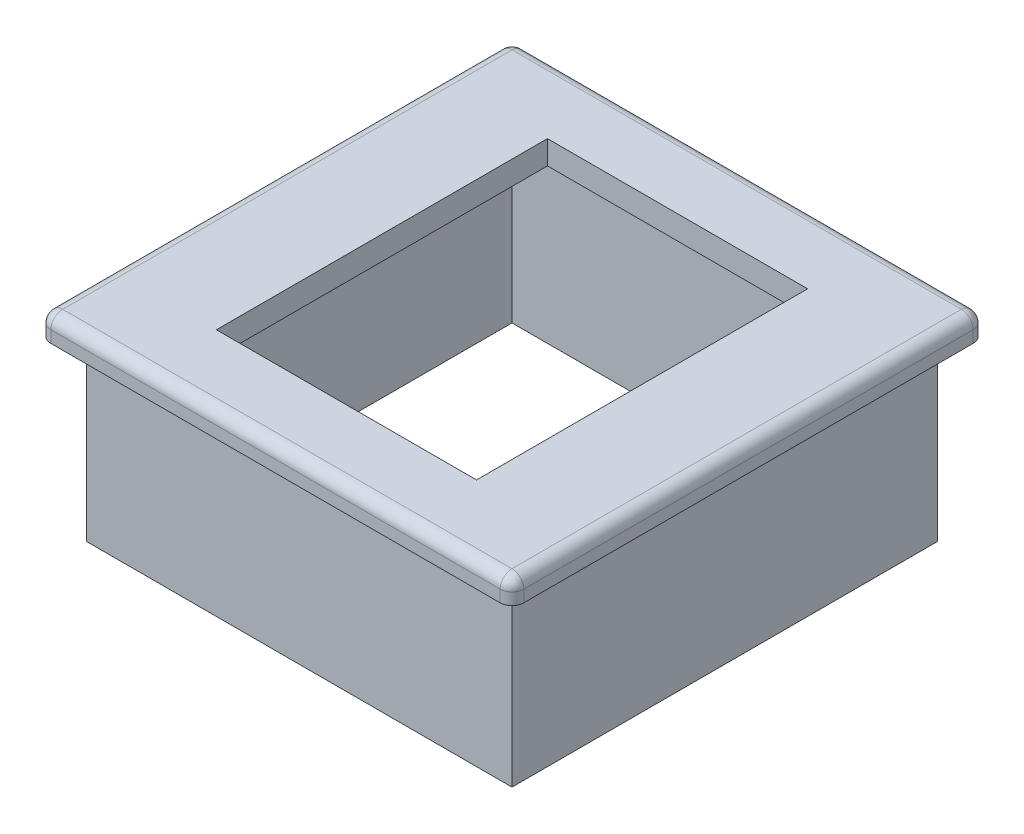
SolidWorks part; units mm, degrees
ref_plane "Front Plane" through (0, 0, 0) normal (0, 0, 1) x (1, 0, 0)
ref_plane "Top Plane" through (0, 0, 0) normal (0, 1, 0) x (1, 0, 0)
ref_plane "Right Plane" through (0, 0, 0) normal (1, 0, 0) x (0, 0, -1)
sketch "Sketch1" plane through (0, 0, 0) normal (0, 1, 0) x (1, 0, 0)
  line L1 (-20, 20) -> (20, 20)
  line L2 (-20, 20) -> (-20, -20)
  line L3 (-20, -20) -> (20, -20)
  line L4 (20, 20) -> (20, -20)
  line L5 (-20, 20) -> (20, -20) construction
  line L6 (-20, -20) -> (20, 20) construction
  line L7 (-11, 14) -> (11, 14)
  line L8 (-11, 14) -> (-11, -14)
  line L9 (-11, -14) -> (11, -14)
  line L10 (11, 14) -> (11, -14)
  line L11 (-11, 14) -> (11, -14) construction
  line L12 (-11, -14) -> (11, 14) construction
  point P0 (0, 0)
  point P6 (0, 0)
  dimension "D1" = 40
  dimension "D2" = 28
  dimension "D3" = 22
extrude "Boss-Extrude1" add sketch "Sketch1" along normal blind 2
sketch "Sketch2" plane through (0, 0, 0) normal (0, -1, 0) x (-1, 0, 0)
  line L1 (-20, 20) -> (20, 20)
  line L2 (-20, 20) -> (-20, -20)
  line L3 (-20, -20) -> (20, -20)
  line L4 (20, 20) -> (20, -20)
  line L5 (18, -18) -> (-18, -18)
  line L6 (18, -18) -> (18, 18)
  line L7 (18, 18) -> (-18, 18)
  line L8 (-18, -18) -> (-18, 18)
  line L9 (-16, 16) -> (16, 16)
  line L10 (-16, 16) -> (-16, -16)
  line L11 (-16, -16) -> (16, -16)
  line L12 (16, 16) -> (16, -16)
  dimension "D1" = 2
  dimension "D2" = 2
  dimension "D3" = 2
  dimension "D4" = 2
  dimension "D5" = 2
  dimension "D6" = 2
  dimension "D7" = 2
  dimension "D8" = 2
extrude "Boss-Extrude2" add sketch "Sketch2" along normal blind 15 contours L8 L5 L6 L7 L9 L12 L11 L10
fillet "Fillet1" radius 1 8 edges at (-20, 1, 20) (20, 2, 0) (0, 2, 20) (-20, 2, 0) (0, 2, -20) (-20, 1, -20) (20, 1, -20) (20, 1, 20)
